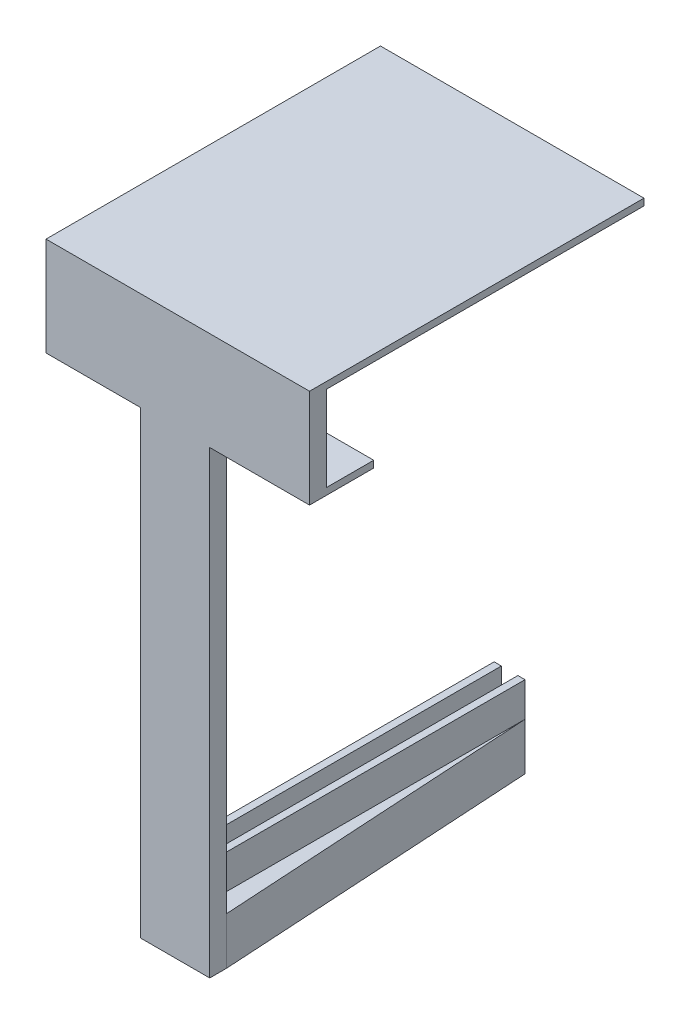
SolidWorks part; units mm, degrees
ref_plane "前基準面" through (0, 0, 0) normal (0, 0, 1) x (1, 0, 0)
ref_plane "上基準面" through (0, 0, 0) normal (0, 1, 0) x (1, 0, 0)
ref_plane "右基準面" through (0, 0, 0) normal (1, 0, 0) x (0, 0, -1)
sketch "草圖1" plane through (0, 0, 0) normal (0, 1, 0) x (1, 0, 0)
  line L0 (-19.5, 0) -> (19.5, 0)
  line L1 (19.5, 0) -> (19.5, 7.099)
  line L2 (-19.5, 0) -> (-19.5, 10.2285)
  line L3 (19.5, 7.099) -> (-12.7014, 7.099)
  line L4 (-12.7014, 7.099) -> (-19.5, 10.2285)
  point P3 (0, 0)
  dimension "D1" = 39
extrude "填料-伸長1" add sketch "草圖1" against normal blind 1
sketch "草圖2" plane through (0, 0, 0) normal (0, 0, 1) x (1, 0, 0)
  line L0 (-19.5, 0) -> (-19.5, -1)
  line L1 (-19.5, -1) -> (19.5, -1)
  line L2 (19.5, -1) -> (19.5, 0)
  line L3 (19.5, 0) -> (-19.5, 0)
extrude "填料-伸長2" add sketch "草圖2" along normal blind 2.5 and the other way blind 47
sketch "草圖3" plane through (0, -1, 0) normal (0, -1, 0) x (1, 0, 0)
  line L0 (-19.5, 2.5) -> (19.5, 2.5)
  line L1 (19.5, 2.5) -> (19.5, 0)
  line L2 (19.5, 2.5) -> (19.5, -47) construction
  line L3 (19.5, 0) -> (-19.5, 0)
  line L4 (-19.5, -47) -> (-19.5, 2.5) construction
  line L5 (-19.5, 0) -> (-19.5, 2.5)
extrude "填料-伸長3" add sketch "草圖3" along normal blind 12.6
sketch "草圖5" plane through (0, -13.6, 0) normal (0, -1, 0) x (1, 0, 0)
  line L0 (-19.5, 2.5) -> (-19.5, 0)
  line L1 (-19.5, 0) -> (19.5, 0)
  line L2 (19.5, 0) -> (19.5, 2.5)
  line L3 (19.5, 2.5) -> (-19.5, 2.5)
extrude "填料-伸長4" add sketch "草圖5" along normal blind 1
sketch "草圖6" plane through (0, 0, 0) normal (0, 0, -1) x (-1, 0, 0)
  line L0 (-19.5, -14.6) -> (-19.5, -13.5963)
  line L1 (-19.5, -14.6) -> (-19.5, -1) construction
  line L2 (-19.5, -13.5963) -> (19.5, -13.5963)
  line L3 (19.5, -14.6) -> (19.5, -1) construction
  line L4 (19.5, -13.5963) -> (19.5, -14.6)
  line L5 (19.5, -14.6) -> (-19.5, -14.6)
extrude "填料-伸長5" add sketch "草圖6" along normal blind 7
sketch "草圖7" plane through (0, -14.6, 0) normal (0, -1, 0) x (1, 0, 0)
  line L0 (-5.4916, 2.5) -> (4.7272, 2.5)
  line L1 (19.5, 2.5) -> (-19.5, 2.5) construction
  line L2 (4.7272, 2.5) -> (4.7272, 0)
  line L3 (4.7272, 0) -> (-5.4916, 0)
  line L4 (-5.4916, 0) -> (-5.4916, 2.5)
extrude "填料-伸長6" add sketch "草圖7" along normal blind 60
sketch "草圖8" plane through (0, -74.6, 0) normal (0, -1, 0) x (1, 0, 0)
  line L0 (-5.4916, 0) -> (-5.4916, 2.5)
  line L1 (-5.4916, 2.5) -> (4.7272, 2.5)
  line L2 (4.7272, 2.5) -> (4.7272, 0)
  line L3 (4.7272, 0) -> (-5.4916, 0)
extrude "填料-伸長7" add sketch "草圖8" along normal blind 8
sketch "草圖9" plane through (0, 0, 0) normal (0, 0, -1) x (-1, 0, 0)
  line L0 (-0.8413, -82.6) -> (1.6057, -82.6)
  line L1 (5.4916, -82.6) -> (-4.7272, -82.6) construction
  line L3 (-0.8413, -82.6) -> (-0.8413, -70.5226)
  line L4 (-0.8413, -70.5226) -> (-1.8974, -70.5226)
  line L5 (-1.8974, -70.5226) -> (-1.8974, -82.6)
  line L6 (-1.8974, -82.6) -> (-0.8413, -82.6)
  line L7 (1.6057, -82.6) -> (1.6057, -70.5226)
  line L8 (1.6057, -70.5226) -> (2.6769, -70.5226)
  line L9 (2.6769, -70.5226) -> (2.6769, -82.6)
  line L10 (2.6769, -82.6) -> (1.6057, -82.6)
  point P5 (0.3822, -82.6)
  line M3 (-4.7272, -82.6) -> (5.4916, -82.6)
extrude "填料-伸長8" add sketch "草圖9" along normal blind 47 contours L4 L5 L3 M3 | L9 L8 L7 M3
sketch "草圖10" plane through (0, -82.6, 0) normal (0, -1, 0) x (1, 0, 0)
  line L0 (-5.4916, 0) -> (-2.6769, -47)
  line L1 (-2.6769, -47) -> (-2.6769, 0)
  line L2 (-2.6769, 0) -> (-5.4916, 0)
  line L3 (1.8974, 0) -> (4.7272, 0)
  line L4 (4.7272, 0) -> (1.8974, -47)
  line L5 (1.8974, -47) -> (1.8974, 0)
extrude "填料-伸長9" add sketch "草圖10" against normal blind 7
